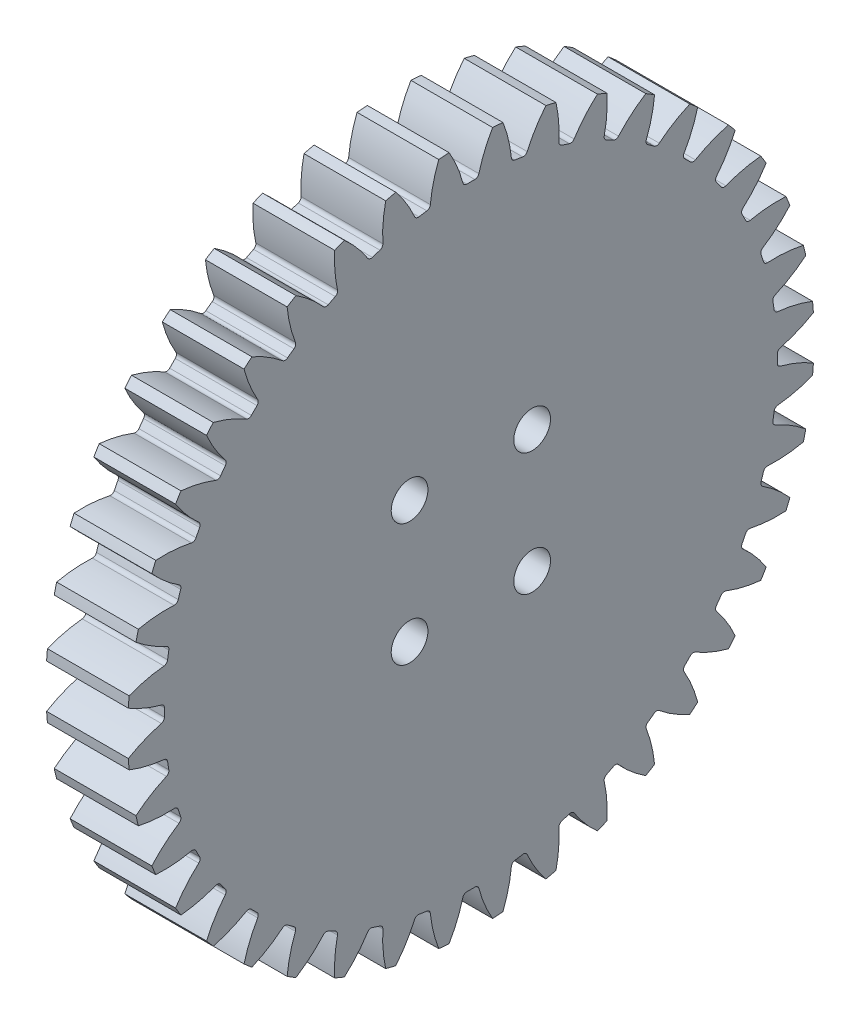
SolidWorks part; units mm, degrees
material "Delrin 2700 NC010, Low Viscosity Acetal Copolymer (SS)"
ref_plane "Plane1" through (0, 0, 0) normal (0, 0, 1) x (1, 0, 0)
ref_plane "Plane2" through (0, 0, 0) normal (0, 1, 0) x (1, 0, 0)
ref_plane "Plane3" through (0, 0, 0) normal (1, 0, 0) x (0, 0, -1)
sketch "HoldingSke" plane through (0, 0, 0) normal (0, 1, 0) x (1, 0, 0)
  line L0 (0, 0) -> (0.383, -0.3214)
  line L1 (-15, 0) -> (100, 0) construction
  line L2 (0, 0) -> (-2.1039, 2.3779)
  line L3 (0, 0) -> (-11.863, 4.5341)
  line L4 (0, 0) -> (6.6156, 5.5511)
  line L5 (0, 0) -> (-46.8476, -17.4728)
  line L6 (0, 0) -> (-4.1448, -2.7965)
  line L7 (-2.1039, 2.3779) -> (8.6586, 51.2059)
  line L8 (-76.2, 54.61) -> (-76.1, 54.61)
  line L9 (-71.009, 38.7566) -> (-53.1078, 45.2721)
  line L10 (-76.2, 71.12) -> (104.1128, 71.12)
  line L11 (0, 0) -> (-5, 0)
  line L12 (-76.2, 101.6) -> (-76.133, 101.6)
  line L13 (24.9733, 27.94) -> (52.9518, 28.4284)
  line L14 (24.9733, 27.94) -> (24.9743, 27.94)
  line L15 (24.9733, 27.94) -> (100.4006, 29.5858)
  line L16 (-63.627, -2) -> (-12.827, -2)
  circle A0 centre (0, 0) radius 0.4
  circle A1 centre (0, 0) radius 37.499
  circle A2 centre (0, 0) radius 37.5
  circle A3 centre (0, 0) radius 0.4
  dimension "MHD" = 74.998
  dimension "Hub_dia" = 75
  dimension "Bore" = 0.8
  dimension "MBD" = 0.8
  dimension "Num_teeth" = 40
  dimension "Pitch" = 0.5
  dimension "Overall_len" = 50
  dimension "Show_teeth" = 40
  dimension "Thickness" = 5
  dimension "OAL" = 50.0001
  dimension "T_dim" = 0.1
  dimension "Ap" = 20
  dimension "H" = 19.05
  dimension "Pitch_radius" = 180.3128
  dimension "Width" = 5
  dimension "Backlash" = 0.067
  dimension "Addendum_fac" = 1
  dimension "Dedendum_fac" = 1.25
  dimension "Clearance_fac" = 0.25
  dimension "Dedendum_add" = 0.001
  dimension "Module" = 2
sketch "BasProSke" plane through (0, 0, 0) normal (0, 1, 0) x (1, 0, 0)
  line L0 (-10, 0) -> (60, 0) construction
  line L1 (0, 0) -> (0, 42)
  line L2 (0, 0) -> (10, 0)
  line L3 (10, 0) -> (10, 42)
  line L4 (10, 42) -> (0, 42)
  dimension "Thickness" = 10
  dimension "Diameter" = 84
revolve "Base-Revolve" add sketch "BasProSke" angle 360 about L0
sketch "TooCutSke" plane through (0, 0, 0) normal (1, 0, 0) x (0, 0, -1)
  line L1 (0, 0) -> (0, 107) construction
  line L2 (0, 0) -> (-1.6876, 39.9644) construction
  line L3 (0, 0) -> (-6.2726, 79.7007) construction
  line L4 (-1.6876, 39.9644) -> (-3.1363, 39.8504) construction
  arc A0 (0.8828, 37.4886) -> (-0.8828, 37.4886) centre (0, 0) ccw
  arc A1 (2.6784, 41.94) -> (-2.6784, 41.94) centre (0, 0) ccw
  circle A2 centre (0, 0) radius 40 construction
  circle A3 centre (0, 0) radius 37.5877 construction
  arc A4 (-0.8828, 37.4886) -> (-2.6784, 41.94) centre (-16.451, 33.7965) ccw
  arc A5 (2.6784, 41.94) -> (0.8828, 37.4886) centre (16.451, 33.7965) ccw
  dimension "Root_dia" = 74.998
  dimension "Overcut_dia" = 84.0508
  dimension "Pitch_dia" = 80
  dimension "Base_dia" = 75.1754
  dimension "Flank_rad" = 16
  dimension "Half_ang" = 4.5
  dimension "Half_CT" = 1.4531
extrude "ToothCut" cut sketch "TooCutSke" along normal through all
fillet "Breaks" [suppressed] radius 0.04
fillet "RootFillets" radius 0.501 2 edges at (5, 37.4886, -0.8828) (5, 37.4886, 0.8828)
pattern_circular "TeethCuts" count 40 every 9 about axis through (-10, 0, 0) along (1, 0, 0) of "ToothCut", "RootFillets", "Breaks"
sketch "HubNeaOneSke" plane through (0, 0, 0) normal (-1, 0, 0) x (0, 0, 1)
  circle A0 centre (0, 0) radius 37.499
  dimension "Diameter" = 74.998
extrude "HubNearOne" [suppressed] add sketch "HubNeaOneSke" along normal blind 40.0001
sketch "HubNeaBotSke" plane through (0, 0, 0) normal (-1, 0, 0) x (0, 0, 1)
  circle A0 centre (0, 0) radius 37.499
  dimension "Diameter" = 74.998
extrude "HubNearBoth" [suppressed] add sketch "HubNeaBotSke" along normal blind 20
ref_plane "FarPln" through (10, 0, 0) normal (1, 0, 0) x (0, 0, -1)
sketch "HubFarSke" plane through (10, 0, 0) normal (1, 0, 0) x (0, 0, -1)
  circle A0 centre (0, 0) radius 37.499
  dimension "Diameter" = 74.998
extrude "HubFar" [suppressed] add sketch "HubFarSke" along normal blind 20
sketch "BorSke" plane through (0, 0, 0) normal (1, 0, 0) x (0, 0, -1)
  circle A0 centre (0, 0) radius 0.4
  dimension "Diameter" = 0.8
extrude "Bore" [suppressed] cut sketch "BorSke" along normal mid plane 100.0001
sketch "KeySke" plane through (0, 0, 0) normal (1, 0, 0) x (0, 0, -1)
  line L0 (-0.05, 0) -> (-0.05, 0.5)
  line L1 (-0.05, 0.5) -> (0.05, 0.5)
  line L2 (0.05, 0.5) -> (0.05, 0)
  line L3 (0, 0) -> (0, 34) construction
  line L4 (-0.05, 0) -> (0.05, 0)
  dimension "Offset" = 0.5
  dimension "Width" = 0.1
extrude "Keyway" [suppressed] cut sketch "KeySke" along normal mid plane 100.0001
pattern_circular "Keyway2" [suppressed] count 2 every 90 about axis through (-10, 0, 0) along (1, 0, 0)
sketch "Sketch1" [suppressed] plane through (6.35, 0, 0) normal (1, 0, 0) x (0, 0, -1)
  line L0 (0, 0) -> (10, 0)
  line L1 (0, 0) -> (-5, 8.6603)
  line L2 (0, 0) -> (-5, -8.6603)
  circle A0 centre (-5, -8.6603) radius 1.5
  circle A1 centre (-5, 8.6603) radius 1.5
  circle A2 centre (10, 0) radius 1.5
  dimension "D6" = 3
  dimension "D7" = 3
  dimension "D8" = 3
  dimension "D1" = 10
  dimension "D2" = 10
  dimension "D3" = 10
  dimension "D4" = 120
  dimension "D5" = 120
extrude "Cut-Extrude1" [suppressed] cut sketch "Sketch1" against normal through all contours A2 | A0 | A1
hole_wizard "#8 Clearance Hole1" positions "Sketch2" profile "Sketch3" hole size "#8" standard "ANSI Inch" end condition through all
sketch "Sketch2" plane through (0, 0, 0) normal (-1, 0, 0) x (0, 0, 1)
  arc A1 (-0.487, -37.4958) -> (0.487, -37.4958) centre (0, 0) ccw construction
  arc A2 (5.3846, -37.1104) -> (6.3467, -36.958) centre (0, 0) ccw construction
  point P0 (-7.5, 7.5)
  point P2 (7.5, 7.5)
  point P4 (-7.5, -7.5)
  point P6 (7.5, -7.5)
  dimension "D1" = 15
  dimension "D2" = 15
  dimension "D3" = 7.5
  dimension "D4" = 7.5
sketch "Sketch3" plane through (0, 7.5, -7.5) normal (0, 1, 0) x (0, 0, 1)
  line L0 (0, 0) -> (0, 10)
  line L1 (0, 10) -> (2.2479, 10)
  line L2 (2.2479, 10) -> (2.2479, 0)
  line L5 (2.2479, 0) -> (0, 0)
  line L11 (0, -6.35) -> (0, 107.95) construction
  dimension "Thru Hole Dia." = 4.4958
  dimension "Thru Hole Depth" = 10
equation "' \"Module@HoldingSke\" = 6.35"
equation "' \"Num_teeth@HoldingSke\" = 12"
equation "' \"Ap@HoldingSke\" =  20"
equation "' \"Ap@HoldingSke\" = 20"
equation "' \"Width@HoldingSke\" = 0.5 * 25.4"
equation "' \"Hub_dia@HoldingSke\"= 1 * 25.4"
equation "' \"Hub_dia@HoldingSke\" = 1 * 25.4"
equation "' \"Overall_len@HoldingSke\" = 1.0 * 25.4"
equation "' \"Bore@HoldingSke\" = 0.75 * 25.4"
equation "' \"T_dim@HoldingSke\" = 0.1 * 25.4"
equation "' \"Width@KeySke\" = 0.25 * 25.4"
equation "' \"Show_teeth@HoldingSke\" = 13"
equation "' \"Backlash@HoldingSke\" = 0.009 * 25.4"
equation "' \"Addendum_fac@HoldingSke\" = 1.0"
equation "' \"Dedendum_fac@HoldingSke\" = 1.25"
equation "' \"Dedendum_add@HoldingSke\" = 0.00005 * 25.4"
equation "' \"Clearance_fac@HoldingSke\" = 0.25"
equation "\"Pitch@HoldingSke\" = 1 / \"Module@HoldingSke\""
equation "\"Overcut_dia@TooCutSke\" = (\"Num_teeth@HoldingSke\" + 2 * \"Addendum_fac@HoldingSke\") / \"Pitch@HoldingSke\" + 0.002 * 25.4"
equation "\"Pitch_dia@TooCutSke\" = \"Num_teeth@HoldingSke\" / \"Pitch@HoldingSke\""
equation "\"Base_dia@TooCutSke\" = \"Num_teeth@HoldingSke\" / \"Pitch@HoldingSke\" * cos((\"Ap@HoldingSke\"  * 3.14159265 / 180))"
equation "\"Root_dia@TooCutSke\" = (\"Num_teeth@HoldingSke\" + 2) / \"Pitch@HoldingSke\" - 2 * (\"Addendum_fac@HoldingSke\" + \"Dedendum_fac@HoldingSke\") / \"Pitch@HoldingSke\" - \"Dedendum_add@HoldingSke\" * 2"
equation "\"Half_ang@TooCutSke\" = 180 / \"Num_teeth@HoldingSke\""
equation "\"Half_CT@TooCutSke\" = \"Num_teeth@HoldingSke\" / \"Pitch@HoldingSke\" * sin((3.14159265 / 2 / \"Num_teeth@HoldingSke\")) / 2 - 7 * \"Backlash@HoldingSke\" / 4"
equation "\"Flank_rad@TooCutSke\" = \"Num_teeth@HoldingSke\" / \"Pitch@HoldingSke\" / 5"
equation "\"Radius@RootFillets\" = \"Clearance_fac@HoldingSke\" / \"Pitch@HoldingSke\" + \"Dedendum_add@HoldingSke\""
equation "\"Break_rad@Breaks\" = 0.02 / \"Pitch@HoldingSke\""
equation "\"Thickness@HoldingSke\" = \"Width@HoldingSke\""
equation "\"OAL@HoldingSke\" = \"Thickness@HoldingSke\""
equation "\"MHD@HoldingSke\" = (\"Num_teeth@HoldingSke\" + 2) / \"Pitch@HoldingSke\" - 2 * (\"Addendum_fac@HoldingSke\" + \"Dedendum_fac@HoldingSke\")  / \"Pitch@HoldingSke\" - \"Dedendum_add@HoldingSke\" * 2"
equation "\"MBD@HoldingSke\" = (\"Num_teeth@HoldingSke\" + 2) / \"Pitch@HoldingSke\" - 2 * (\"Addendum_fac@HoldingSke\" + \"Dedendum_fac@HoldingSke\")  / \"Pitch@HoldingSke\" - \"Dedendum_add@HoldingSke\" * 2 - 0.002 * 25.4"
equation "\"MHD@HoldingSke\" = ((sgn( \"MHD@HoldingSke\" - \"Hub_dia@HoldingSke\" )-1)*( \"MHD@HoldingSke\" - \"Hub_dia@HoldingSke\" ))/-2+ \"Hub_dia@HoldingSke\""
equation "\"MBD@HoldingSke\" = ((sgn( \"MBD@HoldingSke\" - \"Bore@HoldingSke\" )-1)*( \"MBD@HoldingSke\" - \"Bore@HoldingSke\" ))/-2+ \"Bore@HoldingSke\""
equation "\"OAL@HoldingSke\" = ((sgn( \"OAL@HoldingSke\" - \"Overall_len@HoldingSke\" )+1)*( \"OAL@HoldingSke\" - \"Overall_len@HoldingSke\" ))/2 + \"Overall_len@HoldingSke\" + 0.000002 * 25.4"
equation "\"Num_teeth@TeethCuts\" = int( \"Show_teeth@HoldingSke\" ) + 1"
equation "\"Num_teeth@TeethCuts\" = ((sgn( \"Num_teeth@TeethCuts\" - \"Num_teeth@HoldingSke\" )-1)*( \"Num_teeth@TeethCuts\" - \"Num_teeth@HoldingSke\" ))/-2+ \"Num_teeth@HoldingSke\""
equation "\"Num_teeth@TeethCuts\" = ((sgn( \"Num_teeth@TeethCuts\" - 2.0)+1)*( \"Num_teeth@TeethCuts\" - 2.0))/2 +2.0"
equation "\"Angle@TeethCuts\" = 360.0 / \"Num_teeth@HoldingSke\""
equation "\"Diameter@BasProSke\" = (\"Num_teeth@HoldingSke\" + 2 * \"Addendum_fac@HoldingSke\") / \"Pitch@HoldingSke\""
equation "' \"Fillet_rad@BasProSke\" =  \"Thickness@HoldingSke\" * 0.05"
equation "' \"Fillet_rad@BasProSke\" = \"Thickness@HoldingSke\" * 0.05"
equation "\"MHD@HoldingSke\" = ((sgn( \"MHD@HoldingSke\" - \"Root_dia@TooCutSke\" )-1)*( \"MHD@HoldingSke\" - \"Root_dia@TooCutSke\" ))/-2+ \"Root_dia@TooCutSke\""
equation "\"Diameter@HubNeaOneSke\" = \"MHD@HoldingSke\""
equation "\"Length@HubNearOne\" = \"OAL@HoldingSke\" - \"Thickness@BasProSke\""
equation "\"Diameter@HubNeaBotSke\" = \"MHD@HoldingSke\""
equation "\"Length@HubNearBoth\" = ( \"OAL@HoldingSke\" - \"Thickness@BasProSke\" ) / 2.0"
equation "\"Thickness@FarPln\" = \"Thickness@BasProSke\""
equation "\"Diameter@HubFarSke\" = \"MHD@HoldingSke\""
equation "\"Length@HubFar\" = ( \"OAL@HoldingSke\" - \"Thickness@BasProSke\" ) / 2.0"
equation "\"Diameter@BorSke\" = \"MBD@HoldingSke\""
equation "\"D1@Bore\" = \"OAL@HoldingSke\" * 2.0"
equation "\"D1@Keyway\" = \"OAL@HoldingSke\" * 2.0"
equation "\"Offset@KeySke\" = \"T_dim@HoldingSke\" + \"MBD@HoldingSke\" / 2.0"
equation "\"D3@Sketch2\"=\"D1@Sketch2\"/2"
equation "\"D4@Sketch2\"=\"D2@Sketch2\"/2"
